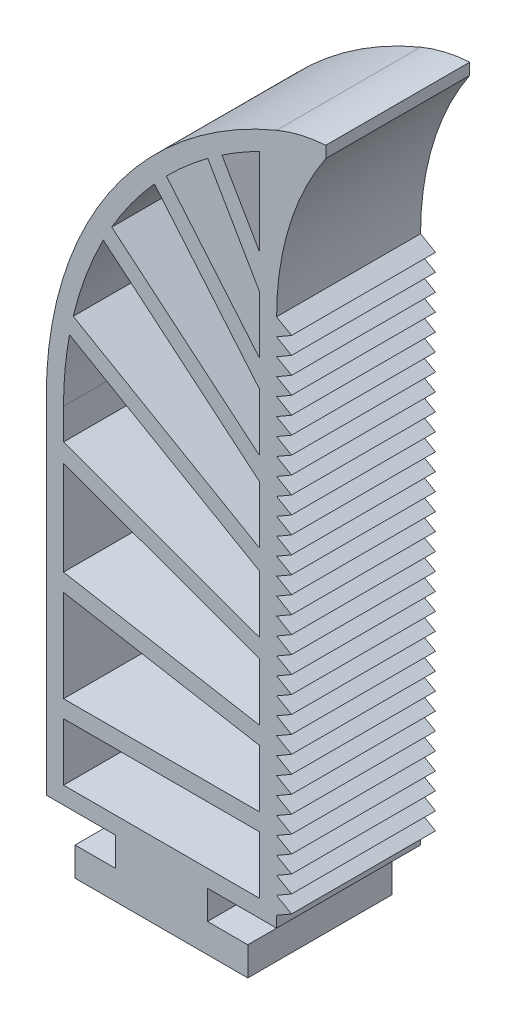
SolidWorks part; units mm, degrees
ref_plane "Front Plane" through (0, 0, 0) normal (0, 0, 1) x (1, 0, 0)
ref_plane "Top Plane" through (0, 0, 0) normal (0, 1, 0) x (1, 0, 0)
ref_plane "Right Plane" through (0, 0, 0) normal (1, 0, 0) x (0, 0, -1)
sketch "Sketch2" plane through (0, 0, 0) normal (0, 0, 1) x (1, 0, 0)
  line L0 (-15, 0) -> (15, 0)
  line L1 (15, 0) -> (15, 5)
  line L2 (15, 5) -> (8, 5)
  line L3 (8, 5) -> (8, 10)
  line L4 (8, 10) -> (20, 10)
  line L5 (20, 10) -> (20, 130)
  line L6 (-15, 0) -> (-15, 5)
  line L7 (-15, 5) -> (-8, 5)
  line L8 (-8, 5) -> (-8, 10)
  line L9 (-8, 10) -> (-20, 10)
  line L10 (-20, 10) -> (-20, 70)
  arc A0 (20, 130) -> (-20, 70) centre (45, 70) ccw
  dimension "D1" = 30
  dimension "D2" = 5
  dimension "D3" = 5
  dimension "D4" = 40
  dimension "D5" = 120
  dimension "D6" = 60
  dimension "D7" = 16
extrude "Boss-Extrude1" add sketch "Sketch2" along normal blind 25
sketch "Sketch3" plane through (0, 0, 25) normal (0, 0, 1) x (1, 0, 0)
  line L0 (-17, 13) -> (17, 13)
  line L1 (17, 13) -> (17, 23)
  line L2 (17, 23) -> (-17, 23)
  line L3 (-17, 23) -> (-17, 13)
  line L4 (-20, 70) -> (-20, 10) construction
  line L5 (20, 10) -> (20, 130) construction
  line L6 (8, 10) -> (20, 10) construction
  dimension "D1" = 3
  dimension "D2" = 3
  dimension "D3" = 3
  dimension "D4" = 10
sketch "Sketch4" plane through (0, 0, 25) normal (0, 0, 1) x (1, 0, 0)
  line L0 (-17, 26) -> (17, 26)
  line L1 (17, 26) -> (17, 36)
  line L2 (17, 36) -> (-17, 41.9951)
  line L3 (-17, 41.9951) -> (-17, 26)
  line L4 (-20, 70) -> (-20, 10) construction
  line L5 (17, 23) -> (-17, 23) construction
  line L6 (20, 10) -> (20, 130) construction
  dimension "D1" = 3
  dimension "D2" = 3
  dimension "D3" = 3
  dimension "D4" = 10
  dimension "D5" = 10
sketch "Sketch5" plane through (0, 0, 25) normal (0, 0, 1) x (1, 0, 0)
  line L0 (-17, 45.0414) -> (17, 39.0463)
  line L1 (17, 39.0463) -> (17, 49.0463)
  line L2 (17, 49.0463) -> (-17, 61.4213)
  line L3 (-17, 61.4213) -> (-17, 45.0414)
  line L4 (-20, 70) -> (-20, 10) construction
  line L5 (20, 10) -> (20, 130) construction
  line L7 (17, 36) -> (-17, 41.9951) construction
  line L8 (-17, 26) -> (17, 26) construction
  dimension "D1" = 3
  dimension "D2" = 3
  dimension "D3" = 3
  dimension "D4" = 20
  dimension "D5" = 10
sketch "Sketch6" plane through (0, 0, 25) normal (0, 0, 1) x (1, 0, 0)
  line L0 (-17, 64.6138) -> (17, 52.2388)
  line L1 (17, 52.2388) -> (17, 62.2388)
  line L2 (17, 62.2388) -> (-15.9667, 81.2721)
  line L3 (-17, 64.6138) -> (-17, 70)
  line L5 (17, 49.0463) -> (-17, 61.4213) construction
  line L6 (-20, 70) -> (-20, 10) construction
  line L7 (20, 10) -> (20, 130) construction
  line L8 (-17, 26) -> (17, 26) construction
  arc A0 (-15.9667, 81.2721) -> (-17, 70) centre (45, 70) ccw
  arc A2 (20, 130) -> (-20, 70) centre (45, 70) ccw construction
  dimension "D1" = 3
  dimension "D2" = 3
  dimension "D3" = 3
  dimension "D4" = 30
  dimension "D5" = 10
extrude "Cut-Extrude1" cut sketch "Sketch3" against normal through all contours L0 L1 L2 L3
extrude "Cut-Extrude2" cut sketch "Sketch4" against normal through all contours L0 L1 L2 L3
extrude "Cut-Extrude3" cut sketch "Sketch5" against normal through all contours L0 L1 L2 L3
extrude "Cut-Extrude4" cut sketch "Sketch6" against normal through all contours L0 L1 L2 A0 L3
sketch "Sketch13" plane through (0, 0, 25) normal (0, 0, 1) x (1, 0, 0)
  line L0 (20, 10) -> (20, 130) construction
  line L1 (28.5436, 132.0151) -> (28.5436, 130.0151)
  line L2 (20, 130) -> (20, 101.9347)
  arc A0 (20, 130) -> (28.5436, 132.0151) centre (30.3921, 105.059) cw
  arc A1 (20, 101.9347) -> (28.5436, 130.0151) centre (70.4182, 101.9347) cw
  arc A2 (20, 130) -> (-20, 70) centre (45, 70) ccw construction
  dimension "D1" = 2
extrude "Boss-Extrude2" add sketch "Sketch13" against normal up to surface (25 mm away) up to face at (-0.7569, 22.1713, 0)
sketch "Sketch15" plane through (0, 0, 25) normal (0, 0, 1) x (1, 0, 0)
  line L0 (20, 101.9347) -> (22.5981, 100.4347)
  line L1 (22.5981, 100.4347) -> (20, 98.9347)
  line L2 (20, 10) -> (20, 101.9347) construction
  line L3 (20, 101.9347) -> (20, 98.9347)
  dimension "D1" = 3
  dimension "D2" = 3
  dimension "D3" = 3
extrude "Boss-Extrude3" add sketch "Sketch15" against normal up to surface (25 mm away) up to face at (4.3889, 42.067, 0)
pattern_linear "LPattern1" count 30 spacing 3 along (0, -1, 0) of "Boss-Extrude3"
sketch "Sketch17" plane through (0, 0, 25) normal (0, 0, 1) x (1, 0, 0)
  line L0 (-15.3142, 84.3595) -> (17, 65.7029)
  line L1 (17, 65.7029) -> (17, 75.7029)
  line L2 (17, 75.7029) -> (-10.0938, 98.4373)
  line L3 (17, 62.2388) -> (-15.9667, 81.2721) construction
  line L4 (17, 52.2388) -> (17, 62.2388) construction
  arc A0 (-10.0938, 98.4373) -> (-15.3142, 84.3595) centre (45, 70) ccw
  arc A1 (-15.9667, 81.2721) -> (-17, 70) centre (45, 70) ccw construction
  dimension "D1" = 10
  dimension "D2" = 3
  dimension "D3" = 10
extrude "Cut-Extrude5" cut sketch "Sketch17" against normal through all contours L2 A0 L0 L1
sketch "Sketch18" plane through (0, 0, 25) normal (0, 0, 1) x (1, 0, 0)
  line L0 (-8.624, 101.1202) -> (17, 79.6191)
  line L1 (17, 79.6191) -> (17, 89.6191)
  line L2 (17, 89.6191) -> (-1.2164, 111.3285)
  line L3 (17, 75.7029) -> (-10.0938, 98.4373) construction
  line L4 (17, 65.7029) -> (17, 75.7029) construction
  arc A0 (-1.2164, 111.3285) -> (-8.624, 101.1202) centre (45, 70) ccw
  arc A1 (-10.0938, 98.4373) -> (-15.3142, 84.3595) centre (45, 70) ccw construction
  dimension "D1" = 3
  dimension "D2" = 10
  dimension "D3" = 10
extrude "Cut-Extrude6" cut sketch "Sketch18" against normal through all
sketch "Sketch19" plane through (0, 0, 25) normal (0, 0, 1) x (1, 0, 0)
  line L0 (0.8519, 113.5309) -> (17, 94.2863)
  line L1 (17, 94.2863) -> (17, 104.2863)
  line L2 (17, 104.2863) -> (8.0507, 119.787)
  line L3 (17, 79.6191) -> (17, 89.6191) construction
  line L5 (17, 89.6191) -> (-1.2164, 111.3285) construction
  arc A0 (8.0507, 119.787) -> (0.8519, 113.5309) centre (45, 70) ccw
  arc A1 (-1.2164, 111.3285) -> (-8.624, 101.1202) centre (45, 70) ccw construction
  dimension "D1" = 10
  dimension "D2" = 3
  dimension "D3" = 10
extrude "Cut-Extrude7" cut sketch "Sketch19" against normal through all contours L2 A0 L0 L1
sketch "Sketch21" plane through (0, 0, 25) normal (0, 0, 1) x (1, 0, 0)
  line L0 (10.5125, 121.5229) -> (17, 110.2863)
  line L1 (17, 110.2863) -> (17, 125.3173)
  line L3 (17, 104.2863) -> (8.0507, 119.787) construction
  line L4 (17, 94.2863) -> (17, 104.2863) construction
  arc A0 (17, 125.3173) -> (10.5125, 121.5229) centre (45, 70) ccw
  arc A1 (8.0507, 119.787) -> (0.8519, 113.5309) centre (45, 70) ccw construction
  point P8 (18, 126.9194)
  dimension "D2" = 3
extrude "Cut-Extrude8" cut sketch "Sketch21" against normal through all
